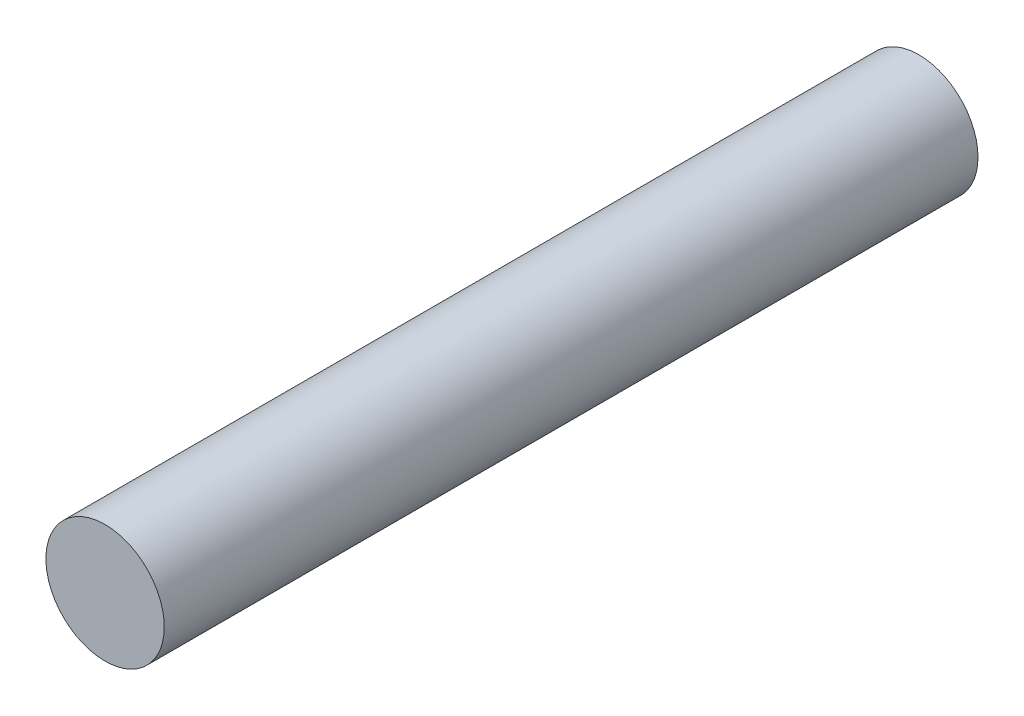
SolidWorks part; units mm, degrees
ref_plane "Front Plane" through (0, 0, 0) normal (0, 0, 1) x (1, 0, 0)
ref_plane "Top Plane" through (0, 0, 0) normal (0, 1, 0) x (1, 0, 0)
ref_plane "Right Plane" through (0, 0, 0) normal (1, 0, 0) x (0, 0, -1)
sketch "Sketch1" plane through (0, 0, 0) normal (0, 0, 1) x (1, 0, 0)
  circle A0 centre (0, 0) radius 4
  dimension "D1" = 8
extrude "Boss-Extrude1" add sketch "Sketch1" along normal blind 55
